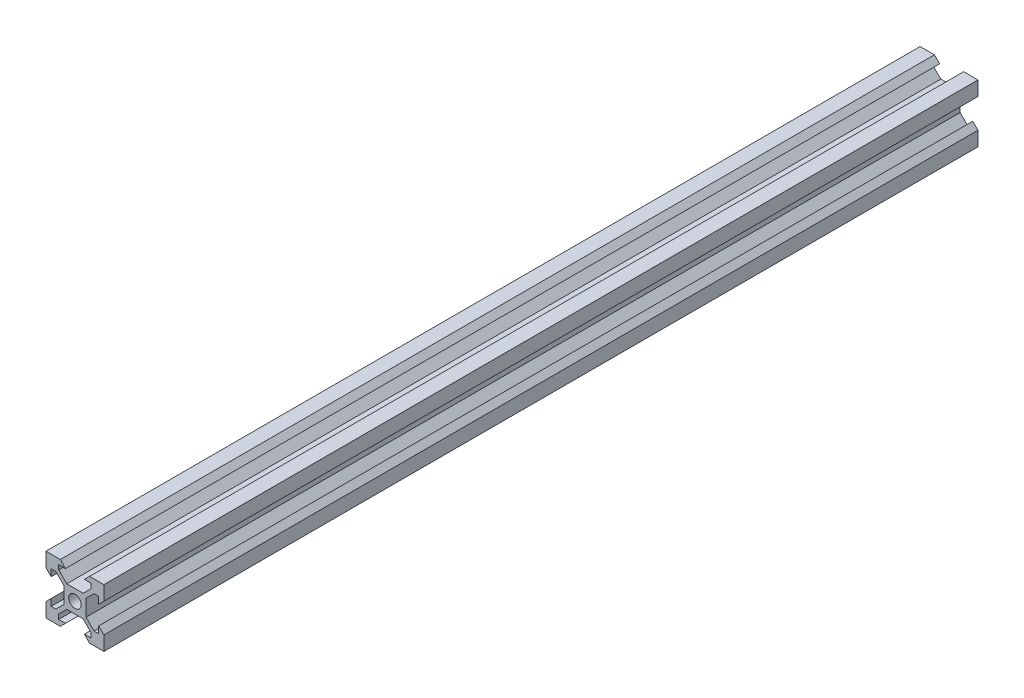
SolidWorks part; units mm, degrees
ref_plane "Alzado" through (0, 0, 0) normal (0, 0, 1) x (1, 0, 0)
ref_plane "Planta" through (0, 0, 0) normal (0, 1, 0) x (1, 0, 0)
ref_plane "Vista lateral" through (0, 0, 0) normal (1, 0, 0) x (0, 0, -1)
sketch "Croquis1" plane through (0, 0, 0) normal (0, 0, 1) x (1, 0, 0)
  line L0 (0, 0) -> (0, -20) construction
  line L2 (0, 0) -> (0, -0.5674)
  line L5 (6.175, -7.1649) -> (6.175, -12.8351)
  line L6 (7.1649, -13.825) -> (12.8351, -13.825)
  line L7 (13.825, -7.1649) -> (13.825, -12.8351)
  line L8 (7.1649, -6.175) -> (12.8351, -6.175)
  line L9 (6.175, -13.825) -> (13.825, -13.825) construction
  line L10 (13.825, -6.175) -> (13.825, -13.825) construction
  line L12 (10, -10) -> (32.1172, -10) construction
  line L13 (13.25, -18.2) -> (15.05, -20)
  line L14 (20, -20) -> (15.6, -20)
  line L15 (20, -20) -> (20, -15.6)
  line L16 (18.2, -15.6) -> (16.5899, -15.6)
  line L32 (15.6, -18.2) -> (15.6, -16.5899)
  line L33 (10, -10) -> (10, -23.2493) construction
  line L34 (4.4, -18.2) -> (4.4, -16.5899)
  line L35 (7.1649, -13.825) -> (4.4, -16.5899)
  line L36 (15.6, -18.2) -> (13.25, -18.2)
  line L38 (15.6, -20) -> (15.05, -20)
  line L40 (15.05, -20) -> (20, -20)
  line L41 (0, -20) -> (20, -20) construction
  line L42 (6.175, -12.8351) -> (3.4101, -15.6)
  line L43 (18.2, -13.25) -> (20, -15.05)
  line L44 (20, -20) -> (18.2, -20)
  line L45 (20, -20) -> (20, -15.05)
  line L48 (20, -15.05) -> (20, -20)
  line L49 (20, 0) -> (20, -20) construction
  line L50 (18.2, -15.6) -> (18.2, -13.25)
  line L51 (12.8351, -13.825) -> (15.6, -16.5899)
  line L52 (13.825, -12.8351) -> (16.5899, -15.6)
  line L53 (1.8, -15.6) -> (3.4101, -15.6)
  line L54 (1.8, -15.6) -> (1.8, -13.25)
  line L55 (1.8, -13.25) -> (0, -15.05)
  line L56 (0, 0) -> (20, 0) construction
  line L57 (0, -20) -> (0, -15.6)
  line L58 (0, -15.6) -> (0, -15.05)
  line L59 (0, -20) -> (4.4, -20)
  line L60 (0, -20) -> (4.95, -20)
  line L61 (6.75, -18.2) -> (4.95, -20)
  line L62 (4.4, -18.2) -> (6.75, -18.2)
  line L63 (1.8, -4.4) -> (3.4101, -4.4)
  line L64 (6.175, -7.1649) -> (3.4101, -4.4)
  line L65 (7.1649, -6.175) -> (4.4, -3.4101)
  line L66 (4.4, -1.8) -> (4.4, -3.4101)
  line L67 (4.4, -1.8) -> (6.75, -1.8)
  line L68 (6.75, -1.8) -> (4.95, 0)
  line L69 (0, 0) -> (4.4, 0)
  line L70 (4.4, 0) -> (4.95, 0)
  line L71 (0, 0) -> (0, -4.4)
  line L72 (0, 0) -> (0, -4.95)
  line L73 (1.8, -6.75) -> (0, -4.95)
  line L74 (1.8, -4.4) -> (1.8, -6.75)
  line L75 (15.6, -1.8) -> (15.6, -3.4101)
  line L76 (12.8351, -6.175) -> (15.6, -3.4101)
  line L77 (13.825, -7.1649) -> (16.5899, -4.4)
  line L78 (18.2, -4.4) -> (16.5899, -4.4)
  line L79 (18.2, -4.4) -> (18.2, -6.75)
  line L80 (18.2, -6.75) -> (20, -4.95)
  line L81 (20, 0) -> (20, -4.4)
  line L82 (20, -4.4) -> (20, -4.95)
  line L83 (20, 0) -> (15.6, 0)
  line L84 (20, 0) -> (15.05, 0)
  line L85 (13.25, -1.8) -> (15.05, 0)
  line L86 (15.6, -1.8) -> (13.25, -1.8)
  line L87 (6.175, -6.175) -> (13.825, -6.175) construction
  line L88 (6.175, -6.175) -> (6.175, -13.825) construction
  circle A0 centre (10, -10) radius 2.15
  point P69 (10, -10)
  dimension "D3" = 4.3
  dimension "D2" = 4
  dimension "D11" = 4.4
  dimension "D15" = 4.4
  dimension "D16" = 6.75
extrude "BoschBase" add sketch "Croquis1" along normal blind 302 contours L86 L75 L76 L8 L65 L66 L67 L68 L70 L69 L2 L71 L72 L73 L74 L63 L64 L5 L42 L53 L54 L55 L58 L57 L59 L60 L61 L62 L34 L35 L6 L51 L32 L36 L13 L38 L40 L14 L15 L45 L43 L50 L16 L52 L7 L77 L78 L79 L80 L82 L81
